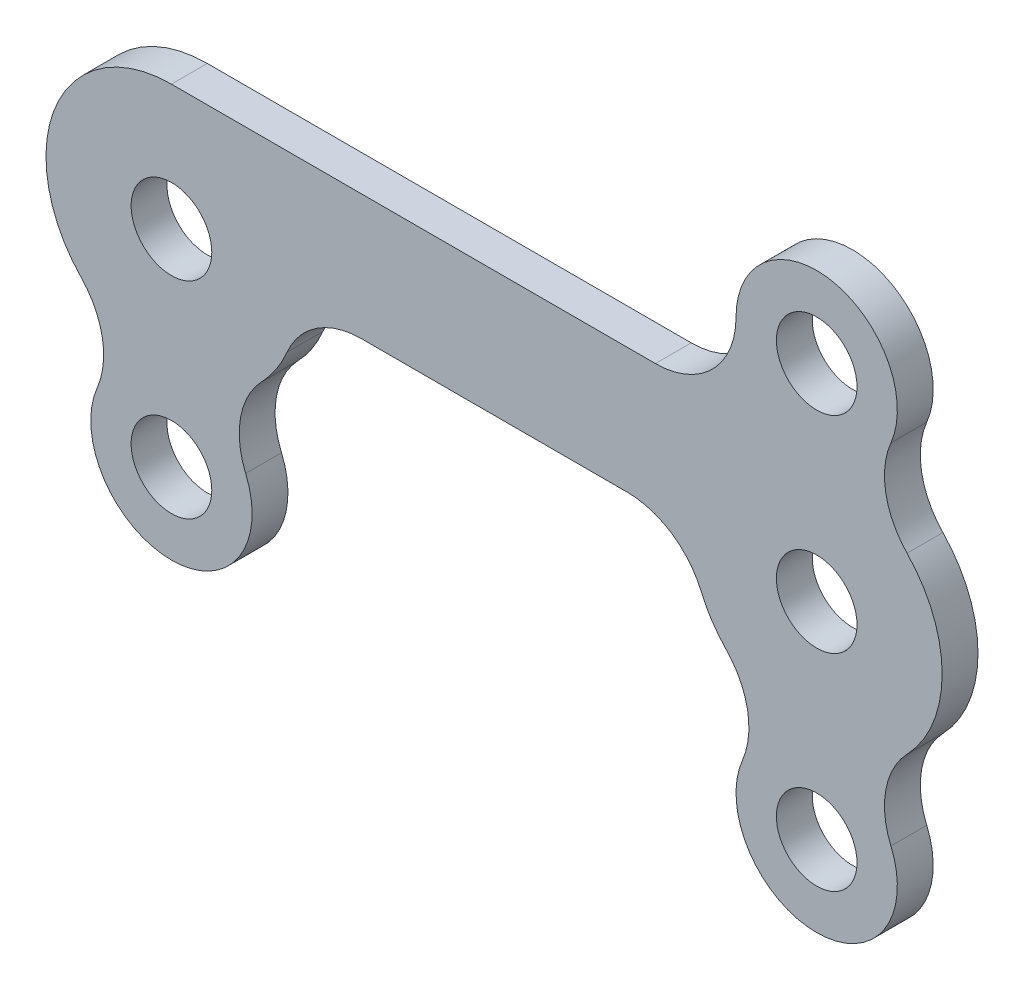
SolidWorks part; units mm, degrees
ref_plane "Front Plane" through (0, 0, 0) normal (0, 0, 1) x (1, 0, 0)
ref_plane "Top Plane" through (0, 0, 0) normal (0, 1, 0) x (1, 0, 0)
ref_plane "Right Plane" through (0, 0, 0) normal (1, 0, 0) x (0, 0, -1)
sketch "Sketch1" plane through (0, 0, 0) normal (0, 0, 1) x (1, 0, 0)
  line L11 (5.5563, 0) -> (23.0188, 0)
  line L12 (0, 5.5563) -> (28.575, 5.5563)
  circle A27 centre (0, 0) radius 5.5563 construction
  circle A28 centre (28.575, 0) radius 5.5562 construction
  arc A29 (0, 5.5563) -> (0, -5.5562) centre (0, 0) ccw
  arc A30 (28.575, -5.5562) -> (28.575, 5.5563) centre (28.575, 0) ccw
  circle A31 centre (0, 0) radius 1.7859
  circle A32 centre (28.575, 0) radius 1.7859
  arc A33 (0, -5.5562) -> (5.5563, 0) centre (0, 0) ccw
  arc A34 (23.0188, 0) -> (28.575, -5.5562) centre (28.575, 0) ccw
  circle A35 centre (0, -9.1281) radius 3.5719
  circle A36 centre (28.575, -9.1281) radius 1.7859
  circle A37 centre (0, -9.1281) radius 1.7859
  circle A38 centre (28.575, -9.1281) radius 3.5719
  circle A39 centre (-6.5741, -6.3327) radius 3.5719
  circle A40 centre (6.5741, -6.3327) radius 3.5719
  circle A41 centre (22.0009, -6.3327) radius 3.5719
  circle A42 centre (35.1491, -6.3327) radius 3.5719
  circle A43 centre (28.575, 9.1281) radius 1.7859
  circle A44 centre (28.575, 9.1281) radius 3.5719
  circle A45 centre (21.4312, 9.1281) radius 3.5719
  circle A46 centre (35.1491, 6.3327) radius 3.5719
  point P0 (0, 0)
  dimension "D8" = 28.575
  dimension "D9" = 11.1125
  dimension "D10" = 3.5719
  dimension "D11" = 7.1437
  dimension "D12" = 3.5719
extrude "Boss-Extrude1" add sketch "Sketch1" along normal blind 1.5875 contours L11 A34 A30 L12 A29 A33 A31 A32 | A35 A37 | A38 A36 | A44 A43 | A45 L12 A44 | A46 A44 A30 | A42 A30 A38 | A41 A38 A34 | A40 A33 A35 | A39 A35 A29
fillet "Fillet1" radius 3.5719 2 edges at (5.5563, 0, 0.7937) (23.0188, 0, 0.7937)
